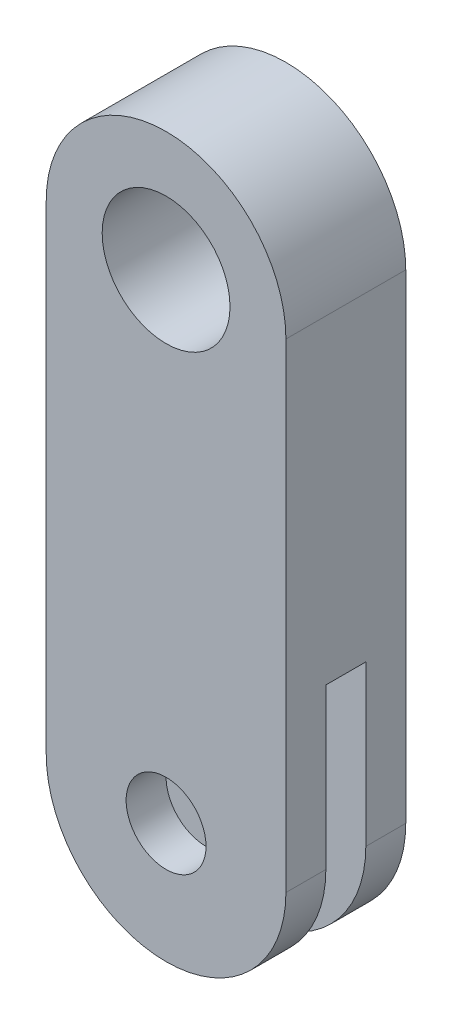
SolidWorks part; units mm, degrees
material "201 Annealed Stainless Steel (SS)"
ref_plane "Front Plane" through (0, 0, 0) normal (0, 0, 1) x (1, 0, 0)
ref_plane "Top Plane" through (0, 0, 0) normal (0, 1, 0) x (1, 0, 0)
ref_plane "Right Plane" through (0, 0, 0) normal (1, 0, 0) x (0, 0, -1)
sketch "Sketch3" plane through (0, 0, 0) normal (0, 0, 1) x (1, 0, 0)
  line L0 (-29.3341, 80.7958) -> (-29.3341, 20.7958)
  line L1 (0.6659, 20.7958) -> (0.6659, 80.7958)
  arc A0 (-29.3341, 20.7958) -> (0.6659, 20.7958) centre (-14.3341, 20.7958) ccw
  arc A1 (0.6659, 80.7958) -> (-29.3341, 80.7958) centre (-14.3341, 80.7958) ccw
  circle A3 centre (-14.3341, 20.7958) radius 5
  circle A5 centre (-14.3341, 80.7958) radius 8
extrude "Boss-Extrude1" add sketch "Sketch3" along normal blind 5
sketch "Sketch4" plane through (0, 0, 0) normal (0, 0, -1) x (-1, 0, 0)
  line L0 (29.3341, 80.7958) -> (29.3341, 40.7958)
  line L1 (-0.6659, 20.7958) -> (-0.6659, 80.7958) construction
  line L2 (29.3341, 80.7958) -> (29.3341, 20.7958) construction
  line L4 (29.3341, 40.7958) -> (-0.6659, 40.7958)
  line L5 (-0.6659, 40.7958) -> (-0.6659, 80.7958)
  circle A1 centre (14.3341, 80.7958) radius 8 construction
  circle A2 centre (14.3341, 20.7958) radius 5 construction
  circle A4 centre (14.3341, 80.7958) radius 8
  arc A5 (-0.6659, 80.7958) -> (29.3341, 80.7958) centre (14.3341, 80.7958) cw
  dimension "D2" = 20
extrude "Boss-Extrude4" add sketch "Sketch4" along normal blind 5
sketch "Sketch5" plane through (0, 0, -5) normal (0, 0, -1) x (-1, 0, 0)
  line L2 (29.3341, 20.7958) -> (29.3341, 80.7958)
  line L3 (-0.6659, 80.7958) -> (-0.6659, 20.7958)
  line L4 (29.3341, 20.7958) -> (29.3341, 80.7958)
  line L5 (-0.6659, 80.7958) -> (-0.6659, 20.7958)
  circle A1 centre (14.3341, 80.7958) radius 8
  circle A2 centre (14.3341, 80.7958) radius 8
  circle A3 centre (14.3341, 20.7958) radius 5
  circle A4 centre (14.3341, 20.7958) radius 5
  arc A6 (-0.6659, 20.7958) -> (29.3341, 20.7958) centre (14.3341, 20.7958) ccw
  arc A7 (29.3341, 80.7958) -> (-0.6659, 80.7958) centre (14.3341, 80.7958) ccw
  arc A8 (-0.6659, 20.7958) -> (29.3341, 20.7958) centre (14.3341, 20.7958) ccw
  arc A9 (29.3341, 80.7958) -> (-0.6659, 80.7958) centre (14.3341, 80.7958) ccw
  dimension "D1" = 0
  dimension "D2" = 0
  dimension "D3" = 0
extrude "Boss-Extrude5" add sketch "Sketch5" along normal blind 5
